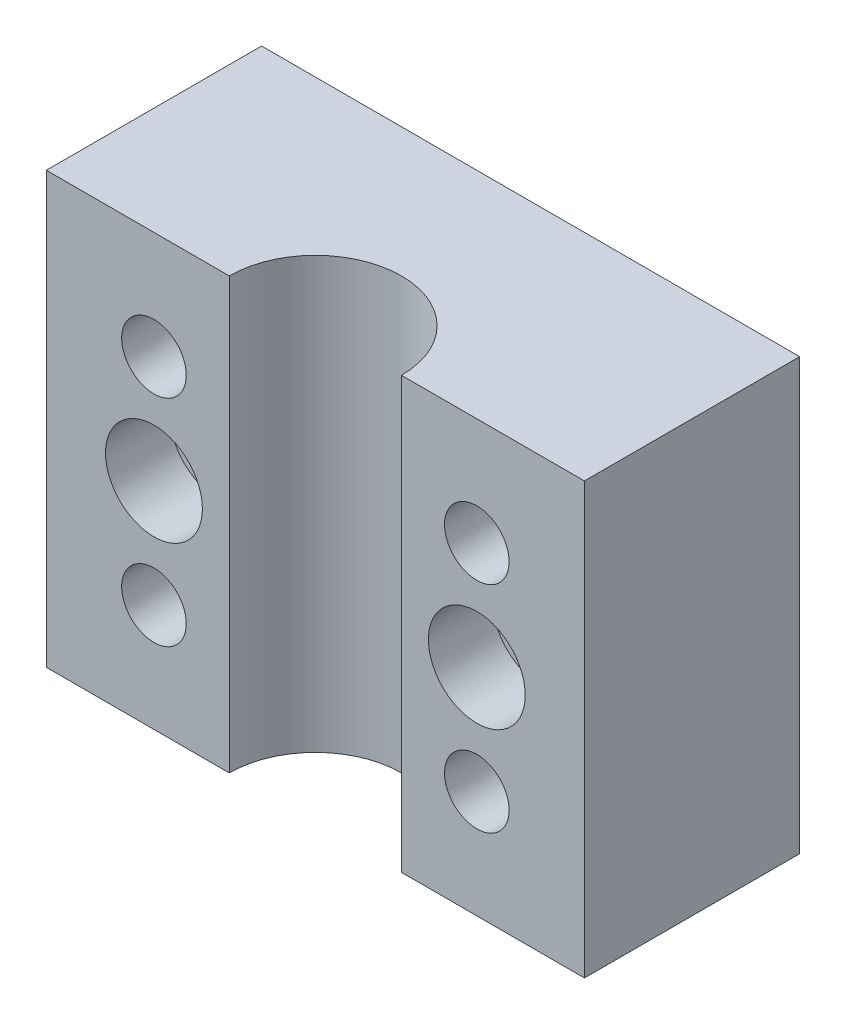
SolidWorks part; units mm, degrees
ref_plane "Front Plane" through (0, 0, 0) normal (0, 0, 1) x (1, 0, 0)
ref_plane "Top Plane" through (0, 0, 0) normal (0, 1, 0) x (1, 0, 0)
ref_plane "Right Plane" through (0, 0, 0) normal (1, 0, 0) x (0, 0, -1)
sketch "Sketch1" plane through (0, 0, 0) normal (0, 0, 1) x (1, 0, 0)
  line L1 (0, 0) -> (50, 0)
  line L2 (0, 0) -> (0, 40)
  line L3 (0, 40) -> (50, 40)
  line L4 (50, 0) -> (50, 40)
  dimension "D1" = 40
  dimension "D2" = 50
extrude "Boss-Extrude1" add sketch "Sketch1" along normal blind 20
sketch "Sketch2" plane through (0, 40, 0) normal (0, 1, 0) x (1, 0, 0)
  line L0 (50, -20) -> (0, -20) construction
  circle A0 centre (25, -20) radius 8
  dimension "D1" = 16
extrude "Cut-Extrude1" cut sketch "Sketch2" against normal blind 43
sketch "Sketch3" plane through (0, 0, 20) normal (0, 0, 1) x (1, 0, 0)
  line L0 (17, 40) -> (0, 40) construction
  line L1 (0, 0) -> (17, 0) construction
  line L2 (33, 0) -> (50, 0) construction
  line L3 (50, 40) -> (33, 40) construction
  line L4 (0, 40) -> (0, 0) construction
  line L5 (50, 0) -> (50, 40) construction
  circle A0 centre (10, 30) radius 3
  circle A1 centre (10, 10) radius 3
  circle A2 centre (40, 30) radius 3
  circle A3 centre (40, 10) radius 3
  dimension "D1" = 6
  dimension "D2" = 6
  dimension "D3" = 6
  dimension "D4" = 6
  dimension "D5" = 10
  dimension "D7" = 10
  dimension "D8" = 10
  dimension "D9" = 10
  dimension "D10" = 10
  dimension "D11" = 10
  dimension "D12" = 10
  dimension "D6" = 10
extrude "Cut-Extrude2" cut sketch "Sketch3" against normal blind 43
sketch "Sketch4" plane through (0, 0, 20) normal (0, 0, 1) x (1, 0, 0)
  line L0 (50, 40) -> (33, 40) construction
  line L1 (17, 40) -> (0, 40) construction
  line L2 (50, 0) -> (50, 40) construction
  line L3 (0, 40) -> (0, 0) construction
  circle A0 centre (10, 20) radius 2.75
  circle A1 centre (40, 20) radius 2.75
  point P8 (8.5, 40)
  point P11 (50, 20)
  dimension "D1" = 5.5
  dimension "D2" = 5.5
  dimension "D3" = 20
  dimension "D4" = 20
  dimension "D5" = 10
  dimension "D6" = 10
extrude "Cut-Extrude3" cut sketch "Sketch4" against normal blind 50
sketch "Sketch5" plane through (0, 0, 20) normal (0, 0, 1) x (1, 0, 0)
  circle A0 centre (10, 20) radius 4.5
  circle A1 centre (40, 20) radius 4.5
  dimension "D1" = 9
  dimension "D2" = 9
extrude "Cut-Extrude4" cut sketch "Sketch5" against normal blind 6
sketch "Sketch6" plane through (0, 0, 0) normal (0, 0, -1) x (-1, 0, 0)
  line L0 (0, 0) -> (-50, 0) construction
  line L1 (-3.9378, 10) -> (-6.9689, 15.25)
  line L2 (-6.9689, 15.25) -> (-13.0311, 15.25)
  line L3 (-13.0311, 15.25) -> (-16.0622, 10)
  line L4 (-16.0622, 10) -> (-13.0311, 4.75)
  line L5 (-13.0311, 4.75) -> (-6.9689, 4.75)
  line L6 (-6.9689, 4.75) -> (-3.9378, 10)
  line L7 (-43.0311, 15.25) -> (-46.0622, 10)
  line L8 (-46.0622, 10) -> (-43.0311, 4.75)
  line L9 (-43.0311, 4.75) -> (-36.9689, 4.75)
  line L10 (-36.9689, 4.75) -> (-33.9378, 10)
  line L11 (-33.9378, 10) -> (-36.9689, 15.25)
  line L12 (-36.9689, 15.25) -> (-43.0311, 15.25)
  line L13 (-36.9689, 24.75) -> (-33.9378, 30)
  line L14 (-33.9378, 30) -> (-36.9689, 35.25)
  line L15 (-36.9689, 35.25) -> (-43.0311, 35.25)
  line L16 (-43.0311, 35.25) -> (-46.0622, 30)
  line L17 (-46.0622, 30) -> (-43.0311, 24.75)
  line L18 (-43.0311, 24.75) -> (-36.9689, 24.75)
  line L19 (-6.9689, 24.75) -> (-3.9378, 30)
  line L20 (-3.9378, 30) -> (-6.9689, 35.25)
  line L21 (-6.9689, 35.25) -> (-13.0311, 35.25)
  line L22 (-13.0311, 35.25) -> (-16.0622, 30)
  line L23 (-16.0622, 30) -> (-13.0311, 24.75)
  line L24 (-13.0311, 24.75) -> (-6.9689, 24.75)
  line L25 (-50, 40) -> (0, 40) construction
  circle A0 centre (-10, 10) radius 5.25 construction
  circle A1 centre (-40, 10) radius 5.25 construction
  circle A2 centre (-40, 30) radius 5.25 construction
  circle A3 centre (-10, 30) radius 5.25 construction
  point P28 (-10, 15.25)
  dimension "D1" = 10.5
  dimension "D2" = 10.5
  dimension "D3" = 10.5
  dimension "D4" = 10.5
  dimension "D5" = 0
  dimension "D6" = 0
  dimension "D7" = 0
  dimension "D8" = 0
extrude "Cut-Extrude5" cut sketch "Sketch6" against normal blind 5
